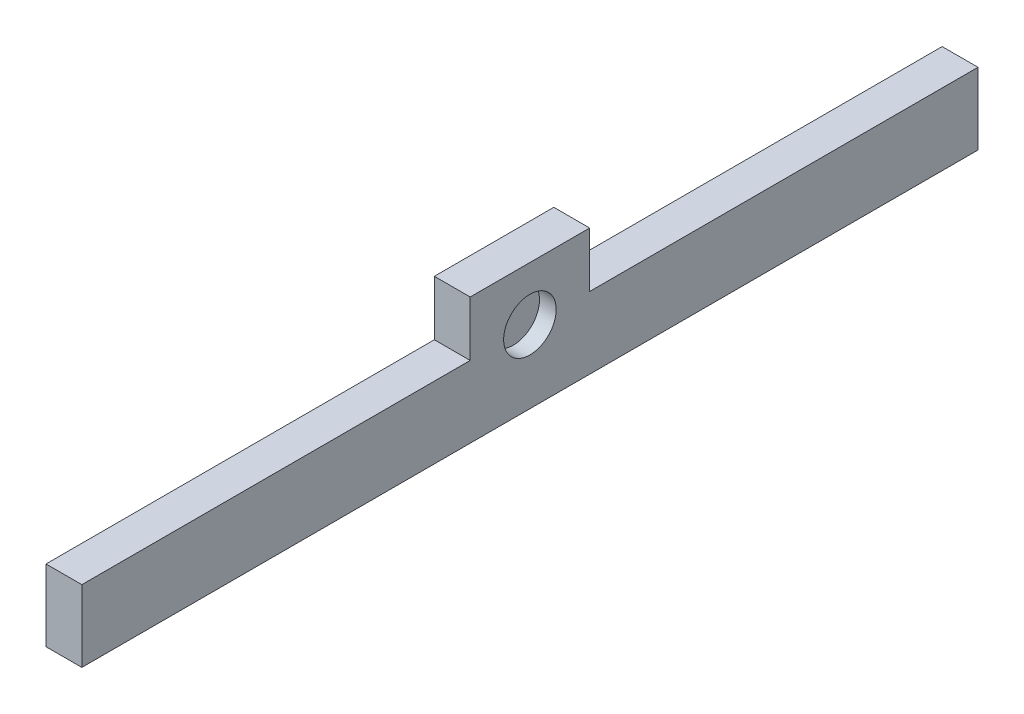
SolidWorks part; units mm, degrees
ref_plane "Alzado" through (0, 0, 0) normal (0, 0, 1) x (1, 0, 0)
ref_plane "Planta" through (0, 0, 0) normal (0, 1, 0) x (1, 0, 0)
ref_plane "Vista lateral" through (0, 0, 0) normal (1, 0, 0) x (0, 0, -1)
sketch "Croquis1" plane through (0, 0, 0) normal (1, 0, 0) x (0, 0, -1)
  line L0 (-187.5, 0) -> (187.5, 0)
  line L2 (-25, 30) -> (-25, 53)
  line L3 (-25, 53) -> (25, 53)
  line L4 (25, 30) -> (25, 53)
  line L7 (-25, 30) -> (-187.5, 30)
  line L8 (-187.5, 0) -> (-187.5, 30)
  line L11 (25, 30) -> (187.5, 30)
  line L12 (187.5, 0) -> (187.5, 30)
  point P0 (0, 0)
  dimension "D4" = 53
  dimension "D1" = 375
  dimension "D2" = 50
  dimension "D3" = 30
extrude "Saliente-Extruir1" add sketch "Croquis1" along normal blind 15
sketch "Croquis2" plane through (15, 0, 0) normal (1, 0, 0) x (0, 0, -1)
  line L1 (-187.5, 0) -> (187.5, 0) construction
  circle A0 centre (0, 30.5) radius 11
  dimension "D2" = 22
  dimension "D1" = 30.5
extrude "Cortar-Extruir1" cut sketch "Croquis2" against normal blind 7
